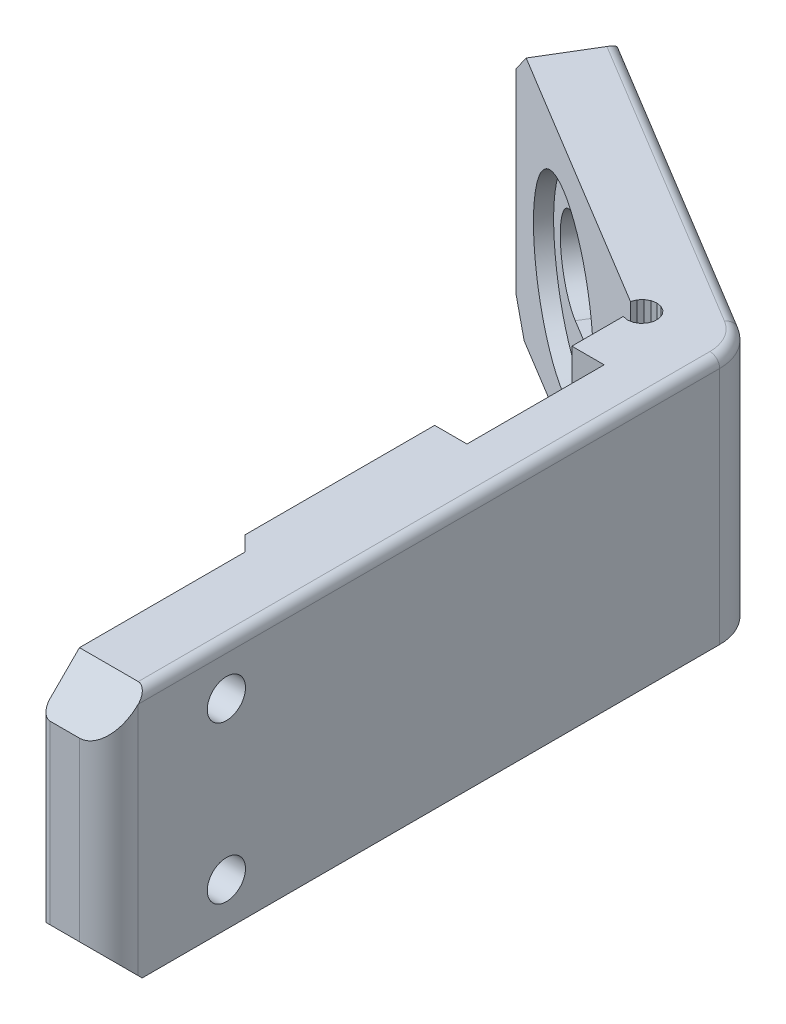
SolidWorks part; units mm, degrees
ref_plane "Front Plane" through (0, 0, 0) normal (0, 0, 1) x (1, 0, 0)
ref_plane "Top Plane" through (0, 0, 0) normal (0, 1, 0) x (1, 0, 0)
ref_plane "Right Plane" through (0, 0, 0) normal (1, 0, 0) x (0, 0, -1)
ref_plane "PY -20.700" through (0, -20.7, 0) normal (0, 1, 0) x (1, 0, 0)
sketch "leg and pad sketch" plane through (0, -20.7, 0) normal (0, 1, 0) x (1, 0, 0)
  line L0 (-0.5513, 30.3327) -> (-0.3673, 30.8194)
  line L1 (-0.3673, 30.8194) -> (-0.028, 31.2139)
  line L2 (-0.028, 31.2139) -> (0.4256, 31.4688)
  line L3 (0.4256, 31.4688) -> (0.939, 31.5534)
  line L4 (0.939, 31.5534) -> (1.4504, 31.4576)
  line L5 (1.4504, 31.4576) -> (1.8983, 31.1928)
  line L6 (1.8983, 31.1928) -> (2.2288, 30.7909)
  line L7 (2.2288, 30.7909) -> (2.4021, 30.3003)
  line L8 (2.4021, 30.3003) -> (2.3973, 29.78)
  line L9 (2.3973, 29.78) -> (2.2152, 29.2926)
  line L10 (2.2152, 29.2926) -> (1.8775, 28.8968)
  line L11 (1.8775, 28.8968) -> (1.4248, 28.6402)
  line L12 (1.4248, 28.6402) -> (0.9118, 28.5536)
  line L13 (0.9118, 28.5536) -> (0.4, 28.6475)
  line L14 (0.4, 28.6475) -> (0.4, -9.98)
  line L15 (0.4, -9.98) -> (1.92, -11.5)
  line L16 (1.92, -11.5) -> (1.92, -32.37)
  line L17 (1.92, -32.37) -> (8.92, -32.37)
  line L18 (8.92, -32.37) -> (8.92, 32.7926)
  line L19 (8.92, 32.7926) -> (-27.2048, 54.5947)
  line L20 (-27.2048, 54.5947) -> (-30.8218, 48.6015)
  line L21 (-30.8218, 48.6015) -> (-0.5513, 30.3327)
extrude "leg and pad" add sketch "leg and pad sketch" along normal mid plane 26
ref_plane "PX 1.350" through (1.35, 0, 0) normal (1, 0, 0) x (0, 0, -1)
sketch "screw head relief sketch" plane through (1.35, 0, 0) normal (1, 0, 0) x (0, 0, -1)
  line L0 (23.4, -12.7) -> (23.4, -6.7)
  line L1 (23.4, -6.7) -> (9.4, -6.7)
  line L2 (9.4, -6.7) -> (9.4, -12.7)
  line L3 (9.4, -12.7) -> (23.4, -12.7)
extrude "screw head relief" cut sketch "screw head relief sketch" against normal mid plane 4.7
sketch "insert flange relief sketch" plane through (0, -20.7, 0) normal (0, 1, 0) x (1, 0, 0)
  line L0 (-18.3249, 39.8914) -> (-17.0331, 42.0318)
  line L1 (-17.0331, 42.0318) -> (-9.3276, 37.3814)
  line L2 (-9.3276, 37.3814) -> (-10.6194, 35.241)
  line L3 (-10.6194, 35.241) -> (-18.3249, 39.8914)
revolve "insert flange relief" cut sketch "insert flange relief sketch" angle 360 about L0
sketch "M6 slot end 1 sketch" plane through (0, -20.7, 0) normal (0, 1, 0) x (1, 0, 0)
  line L0 (-20.4653, 41.1832) -> (-15.8149, 48.8886)
  line L1 (-15.8149, 48.8886) -> (-11.9621, 46.5634)
  line L2 (-11.9621, 46.5634) -> (-16.6125, 38.858)
  line L3 (-16.6125, 38.858) -> (-20.4653, 41.1832)
revolve "M6 slot end 1" cut sketch "M6 slot end 1 sketch" angle 360 about L0
sketch "M6 slot end 2 sketch" plane through (0, -20.7, 0) normal (0, 1, 0) x (1, 0, 0)
  line L0 (-16.1845, 38.5996) -> (-11.5341, 46.3051)
  line L1 (-11.5341, 46.3051) -> (-7.6813, 43.9799)
  line L2 (-7.6813, 43.9799) -> (-12.3317, 36.2744)
  line L3 (-12.3317, 36.2744) -> (-16.1845, 38.5996)
revolve "M6 slot end 2" cut sketch "M6 slot end 2 sketch" angle 360 about L0
sketch "M6 slot middle sketch" plane through (0, -20.7, 0) normal (0, 1, 0) x (1, 0, 0)
  line L0 (-16.1845, 38.5996) -> (-20.4653, 41.1832)
  line L1 (-20.4653, 41.1832) -> (-15.8149, 48.8886)
  line L2 (-15.8149, 48.8886) -> (-11.5341, 46.3051)
  line L3 (-11.5341, 46.3051) -> (-16.1845, 38.5996)
extrude "M6 slot middle" cut sketch "M6 slot middle sketch" against normal mid plane 9
ref_plane "PX 5.420" through (5.42, 0, 0) normal (1, 0, 0) x (0, 0, -1)
sketch "screw holes sketch" plane through (5.42, 0, 0) normal (1, 0, 0) x (0, 0, -1)
  circle A0 centre (-20.375, -28.7) radius 1.95
  circle A1 centre (-20.375, -12.7) radius 1.95
extrude "screw holes" cut sketch "screw holes sketch" against normal mid plane 9
chamfer "leg top corners" distance 4 angle 45 2 edges at (5.42, -7.7, 32.37) (5.42, -33.7, 32.37)
chamfer "pad end corners" distance 4 angle 45 2 edges at (-29.0133, -7.7, -51.5981) (-29.0133, -33.7, -51.5981)
fillet "outside of the bend" radius 5 1 edges at (8.92, -20.7, -32.7926)
fillet "leg top outer edge" radius 3 1 edges at (8.92, -20.7, 32.37)
fillet "pad end outer edge" radius 3 1 edges at (-27.2048, -20.7, -54.5947)
fillet "leg top inner edge" radius 1 1 edges at (1.92, -20.7, 32.37)
fillet "pad end inner edge" radius 1 1 edges at (-30.8218, -20.7, -48.6015)
chamfer "bed face chamfer" distance 0.6 angle 45 6 edges at (-13.9742, -33.7, -38.4337) (-8.6383, -33.7, -43.3894) (1.92, -33.7, 19.935) (0.4, -33.7, -9.3337) (8.2742, -33.7, -32.4281) (8.92, -33.7, -0.8001)
fillet "top face edge" radius 1 3 edges at (-8.6383, -7.7, -43.3894) (8.2742, -7.7, -32.4281) (8.92, -7.7, -0.8001)
equation "\"diffL\" = 608.8mm"
equation "\"diffW\" = 329.4mm"
equation "\"diffT\" = 2.9mm"
equation "\"chanSlotW\" = 12.9mm"
equation "\"chanSlotDepth\" = 11.13mm"
equation "\"chanFloor\" = 1.57mm"
equation "\"chanLeg\" = 12.7mm"
equation "\"lightL\" = 605mm"
equation "\"lightW\" = 331mm"
equation "\"lightH\" = 92mm"
equation "\"lightSideFlat\" = 30mm"
equation "\"lightSlopeLen\" = 33.1mm"
equation "\"lightWingDepth\" = 47.9mm"
equation "\"lightWingFlat\" = 90.2mm"
equation "\"lightChanW\" = 99.6mm"
equation "\"lightChanStand\" = 44.1mm"
equation "\"insFlangeD\" = 12.3mm"
equation "\"insFromEnd\" = 20.7mm"
equation "\"insUpSlope\" = 20.8mm"
equation "\"gaugeH\" = 10mm"
equation "\"gaugeStepLen\" = 14mm"
equation "\"gaugeStepW0\" = 13.1mm"
equation "\"gaugeStepDW\" = 0.2mm"
equation "\"gaugeSteps\" = 5mm"
equation "\"gaugeHandleLen\" = 30mm"
equation "\"gaugeHandleW\" = 24mm"
equation "\"gaugeSlot0\" = 3mm"
equation "\"gaugeSlotD\" = 0.1mm"
equation "\"gaugeSlotDepth\" = 8mm"
equation "\"gap\" = 25.4mm"
equation "\"edgeL\" = 1mm"
equation "\"edgeW\" = 0.75mm"
equation "\"proud\" = 1.5mm"
equation "\"seatClr\" = 0.15mm"
equation "\"tongueClrZ\" = 0.1mm"
equation "\"tongueClrX\" = 0.25mm"
equation "\"tongueLen\" = 30mm"
equation "\"armSide\" = 45mm"
equation "\"armEnd\" = 20mm"
equation "\"cornerCham\" = 3mm"
equation "\"brkW\" = 26mm"
equation "\"brkT\" = 7mm"
equation "\"brkSeatClr\" = 0.2mm"
equation "\"brkScrewSpan\" = 16mm"
equation "\"pilotD\" = 2.7mm"
equation "\"pilotDepth\" = 10mm"
equation "\"screwClrD\" = 3.9mm"
equation "\"jogBelow\" = 4mm"
equation "\"padT\" = 7mm"
equation "\"padLen\" = 31mm"
equation "\"m6Clr\" = 7mm"
equation "\"m6Slot\" = 3mm"
equation "\"flangeRelD\" = 17mm"
equation "\"flangeRelDepth\" = 1.5mm"
equation "\"relLen\" = 7mm"
equation "\"relDepth\" = 4mm"
equation "\"relLand\" = 2mm"
equation "\"knockN\" = 100mm"
equation "\"petgcfE\" = 3000mm"
equation "\"mockExtent\" = 110mm"
equation "\"relZnear\" = 9.4mm"
equation "\"relZfar\" = 23.4mm"
equation "\"headD\" = 8mm"
equation "\"headH\" = 2.5mm"
equation "\"headFromEnd\" = 6.8mm"
equation "\"headBack\" = 16.4mm"
equation "\"sideClr\" = 0.4mm"
equation "\"cornerRelR\" = 1.5mm"
equation "\"cornerRelBack\" = 0.6mm"
equation "\"endHeadH\" = 2.8mm"
equation "\"footClr\" = 1.2mm"
equation "\"footEndClr\" = 3.5mm"
equation "\"footLift\" = 6mm"
equation "\"footBlockClr\" = 0.5mm"
equation "\"footBack\" = 50mm"
equation "\"footFwd\" = 10mm"
equation "\"footBraceEnd\" = 3mm"
equation "\"footLoadN\" = 25mm"
equation "\"spacerLen\" = 60mm"
equation "\"spacerShort\" = 0.5mm"
equation "\"spacerCham\" = 0.8mm"
equation "\"spacerPerSide\" = 3mm"
equation "\"spacerPerEnd\" = 1mm"
equation "\"toolR\" = 9mm"
equation "\"visR\" = 4mm"
equation "\"edgeR\" = 1mm"
equation "\"bendOutR\" = 5mm"
equation "\"insideR\" = 2.5mm"
equation "\"footCornerR\" = 10mm"
equation "\"footFrontR\" = 8mm"
equation "\"braceKinkR\" = 12mm"
equation "\"bedCham\" = 1mm"
equation "\"bedChamSmall\" = 0.6mm"
equation "\"soleTopR\" = 2mm"
equation "\"cornerR\" = 6mm"
equation "\"rimInR\" = 1mm"
equation "\"insFlangeH\" = 1mm"
